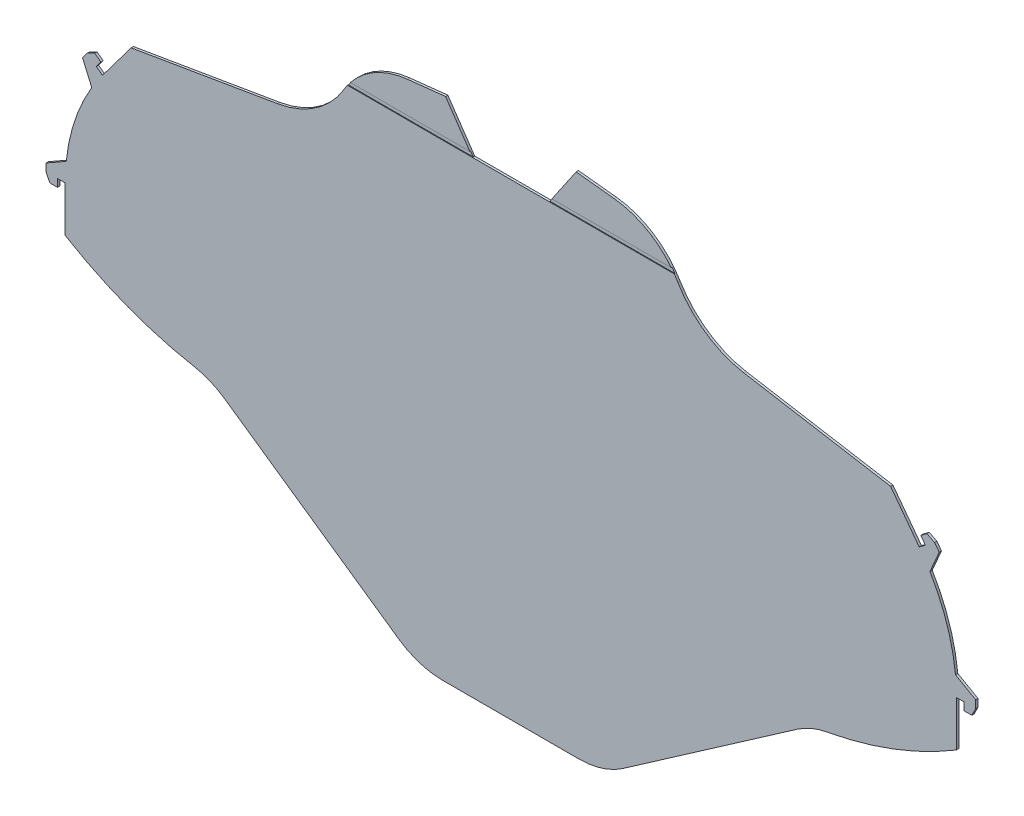
SolidWorks part; units mm, degrees
ref_plane "Front Plane" through (0, 0, 0) normal (0, 0, 1) x (1, 0, 0)
ref_plane "Top Plane" through (0, 0, 0) normal (0, 1, 0) x (1, 0, 0)
ref_plane "Right Plane" through (0, 0, 0) normal (1, 0, 0) x (0, 0, -1)
sketch "Sketch1" plane through (0, 0, 0) normal (0, 0, 1) x (1, 0, 0)
  line L0 (-24, -91.7648) -> (24, -91.7648)
  line L1 (0, 0) -> (0, -91.7648) construction
  line L2 (-10, 0) -> (-17, 10.2352)
  line L5 (-100.1804, -19.9556) -> (-60.7439, -13.2648)
  line L7 (-24, -91.7648) -> (-78.2662, -84.0567)
  line L8 (-17, 10.2352) -> (-26.9419, 9.1584)
  line L13 (-122.5, -58.7648) -> (122.5, -58.7648) construction
  line L14 (-60.7439, -13.2648) -> (-60.7439, -58.7648) construction
  line L15 (-113.5977, -28.7648) -> (-113.5977, -58.7648) construction
  line L16 (-10, 0) -> (10, 0)
  line L17 (10, 0) -> (17, 10.2352)
  line L18 (113.5977, -28.7648) -> (113.5977, -58.7648) construction
  line L19 (60.7439, -13.2648) -> (60.7439, -58.7648) construction
  line L20 (17, 10.2352) -> (26.9419, 9.1584)
  line L21 (24, -91.7648) -> (78.2662, -84.0567)
  line L22 (100.1804, -19.9556) -> (60.7439, -13.2648)
  line L23 (-17, 10.2352) -> (17, 10.2352) construction
  line L24 (0, 10.2352) -> (0, 0) construction
  arc A0 (-26.9419, 9.1584) -> (-43.4614, -1.4344) centre (-24.5729, -12.7137) ccw
  arc A1 (-43.4614, -1.4344) -> (-60.7439, -13.2648) centre (-64.9257, 11.383) cw
  arc A2 (-113.5977, -28.7648) -> (-100.1804, -19.9556) centre (-96.8349, -39.6739) cw
  arc A3 (-122.5, -58.7648) -> (-113.5977, -28.7648) centre (-67.5, -58.7648) cw
  arc A8 (-122.5, -58.7648) -> (-115.7111, -70.7648) centre (-108.5, -58.7648) ccw
  arc A9 (-115.7111, -70.7648) -> (-78.2662, -84.0567) centre (-64.2032, 14.9495) ccw
  arc A10 (115.7111, -70.7648) -> (78.2662, -84.0567) centre (64.2032, 14.9495) cw
  arc A11 (122.5, -58.7648) -> (115.7111, -70.7648) centre (108.5, -58.7648) cw
  arc A12 (122.5, -58.7648) -> (113.5977, -28.7648) centre (67.5, -58.7648) ccw
  arc A13 (113.5977, -28.7648) -> (100.1804, -19.9556) centre (96.8349, -39.6739) ccw
  arc A14 (43.4614, -1.4344) -> (60.7439, -13.2648) centre (64.9257, 11.383) ccw
  arc A15 (26.9419, 9.1584) -> (43.4614, -1.4344) centre (24.5729, -12.7137) cw
  dimension "D5" = 55
  dimension "D7" = 20
  dimension "D9" = 25
  dimension "D11" = 22
  dimension "D12" = 14
  dimension "D19" = 100
  dimension "D2" = 50.7439
  dimension "D3" = 102
  dimension "D4" = 10
  dimension "D6" = 14
  dimension "D8" = 40
  dimension "D10" = 58.7648
  dimension "D13" = 188.084
  dimension "D14" = 12.4
  dimension "D15" = 45.5
  dimension "D16" = 30
  dimension "D17" = 33
  dimension "D18" = 118.187
  dimension "D20" = 20
extrude "Main Shape" add sketch "Sketch1" along normal blind 0.6
sketch "Sketch2" plane through (0, 0, 0.6) normal (0, 0, 1) x (1, 0, 0)
  line L0 (0, 0) -> (0, -91.7648) construction
  line L1 (-24, -91.7648) -> (24, -91.7648) construction
  line L5 (-121, -58.7648) -> (-121, -56.7648)
  line L15 (-116, -58.7648) -> (-116, -70.5864)
  line L23 (113.5111, -43.4277) -> (119.6776, -41.3722) construction
  line L24 (113.5111, -43.4277) -> (106.4062, -22.1128) construction
  line L25 (110.3, -26.6648) -> (111.5, -28.2648)
  line L41 (-106.3, -29.6648) -> (-98.8487, -19.7297)
  line L42 (-60.7439, -13.2648) -> (-100.1804, -19.9556) construction
  line L43 (-98.8487, -19.7297) -> (-100.1804, -19.9556)
  line L44 (-116, -58.7648) -> (-118, -58.7648)
  line L45 (-118, -58.7648) -> (-118, -60.7648)
  line L46 (-118, -60.7648) -> (-120, -60.7648)
  line L47 (-120, -60.7648) -> (-121, -58.7648)
  line L48 (-121, -56.7648) -> (-115.7423, -53.7714)
  line L49 (-113.5111, -43.4277) -> (-106.4062, -22.1128) construction
  line L50 (-113.5111, -43.4277) -> (-119.6776, -41.3722) construction
  line L51 (-111.5, -28.2648) -> (-109.0898, -33.8141)
  line L52 (-108.3, -25.6648) -> (-110.3, -26.6648)
  line L53 (-106.7, -26.8648) -> (-108.3, -25.6648)
  line L54 (-107.9, -28.4648) -> (-106.7, -26.8648)
  line L55 (-106.3, -29.6648) -> (-107.9, -28.4648)
  line L56 (-110.3, -26.6648) -> (-111.5, -28.2648)
  line L57 (106.3, -29.6648) -> (107.9, -28.4648)
  line L58 (107.9, -28.4648) -> (106.7, -26.8648)
  line L59 (106.7, -26.8648) -> (108.3, -25.6648)
  line L60 (108.3, -25.6648) -> (110.3, -26.6648)
  line L61 (111.5, -28.2648) -> (109.0898, -33.8141)
  line L62 (121, -56.7648) -> (115.7423, -53.7714)
  line L63 (120, -60.7648) -> (121, -58.7648)
  line L64 (118, -60.7648) -> (120, -60.7648)
  line L65 (118, -58.7648) -> (118, -60.7648)
  line L66 (116, -58.7648) -> (118, -58.7648)
  line L67 (98.8487, -19.7297) -> (100.1804, -19.9556)
  line L68 (106.3, -29.6648) -> (98.8487, -19.7297)
  line L69 (116, -58.7648) -> (116, -70.5864)
  line L70 (121, -58.7648) -> (121, -56.7648)
  arc A9 (-106.3, -29.6648) -> (-116, -58.7648) centre (-67.5, -58.7648) ccw construction
  arc A11 (-113.5977, -28.7648) -> (-122.5, -58.7648) centre (-67.5, -58.7648) ccw construction
  arc A12 (-115.7423, -53.7714) -> (-109.0898, -33.8141) centre (-67.5, -58.7648) cw
  arc A13 (-107.5, -28.7648) -> (-117.5, -58.7648) centre (-67.5, -58.7648) ccw construction
  arc A14 (-105.1, -30.5648) -> (-114.5, -58.7648) centre (-67.5, -58.7648) ccw construction
  arc A15 (-105.1, -30.5648) -> (-107.5, -28.7648) centre (-106.3, -29.6648) ccw construction
  arc A16 (-117.5, -58.7648) -> (-114.5, -58.7648) centre (-116, -58.7648) ccw construction
  arc A18 (106.3, -29.6648) -> (116, -58.7648) centre (67.5, -58.7648) cw construction
  arc A19 (107.5, -28.7648) -> (117.5, -58.7648) centre (67.5, -58.7648) cw construction
  arc A21 (105.1, -30.5648) -> (114.5, -58.7648) centre (67.5, -58.7648) cw construction
  arc A22 (105.1, -30.5648) -> (107.5, -28.7648) centre (106.3, -29.6648) cw construction
  arc A23 (117.5, -58.7648) -> (114.5, -58.7648) centre (116, -58.7648) cw construction
  arc A24 (122.5, -58.7648) -> (116, -70.5864) centre (108.5, -58.7648) cw
  arc A25 (113.5977, -28.7648) -> (122.5, -58.7648) centre (67.5, -58.7648) cw
  arc A26 (100.1804, -19.9556) -> (113.5977, -28.7648) centre (96.8349, -39.6739) cw
  arc A33 (-122.5, -58.7648) -> (-115.7111, -70.7648) centre (-108.5, -58.7648) ccw construction
  arc A34 (-100.1804, -19.9556) -> (-113.5977, -28.7648) centre (-96.8349, -39.6739) ccw construction
  arc A35 (-100.1804, -19.9556) -> (-113.5977, -28.7648) centre (-96.8349, -39.6739) ccw
  arc A36 (-113.5977, -28.7648) -> (-122.5, -58.7648) centre (-67.5, -58.7648) ccw
  arc A37 (-122.5, -58.7648) -> (-116, -70.5864) centre (-108.5, -58.7648) ccw
  arc A38 (115.7423, -53.7714) -> (109.0898, -33.8141) centre (67.5, -58.7648) ccw
  point P24 (-113.5111, -43.4277)
  point P46 (113.5111, -43.4277)
  dimension "D1" = 1.5
  dimension "D2" = 5
  dimension "D3" = 2
  dimension "D7" = 5
  dimension "D4" = 2
  dimension "D5" = 2
  dimension "D6" = 2
  dimension "D8" = 5
extrude "Tabs" cut sketch "Sketch2" against normal through all both and the other way through all
sketch "Sketch4" plane through (0, 0, 0.6) normal (0, 0, 1) x (1, 0, 0)
  line L6 (-45, 0) -> (45, 0)
  line L8 (45, 0) -> (45, 1)
  line L9 (45, 1) -> (-45, 1)
  line L10 (-45, 1) -> (-45, 0)
  point P3 (0, 0)
  dimension "D1" = 90
  dimension "D2" = 1
extrude "Tab Fold Line" cut sketch "Sketch4" against normal blind 0.2
sketch "Sketch5" plane through (0, 0, 0.6) normal (0, 0, 1) x (1, 0, 0)
  line L0 (-78.2662, -84.0567) -> (-24, -121.7648)
  line L1 (-24, -121.7648) -> (24, -121.7648)
  line L2 (24, -121.7648) -> (78.2662, -84.0567)
  line L3 (-78.2662, -84.0567) -> (-24, -91.7648) construction
  line L4 (24, -91.7648) -> (78.2662, -84.0567) construction
  line L5 (-24, -91.7648) -> (24, -91.7648) construction
  line L6 (24, -91.7648) -> (78.2662, -84.0567)
  line L7 (-24, -91.7648) -> (24, -91.7648)
  line L8 (-78.2662, -84.0567) -> (-24, -91.7648)
  point P6 (0, 0)
  point P7 (0, 0)
  point P10 (19, -135.0911)
  point P12 (-19, -128.8488)
  dimension "D1" = 30
extrude "Chin guard" add sketch "Sketch5" against normal up to surface (0.6 mm away) up to face at (0, -39.2266, 0)
fillet "Fillet1" radius 20 4 edges at (-78.2662, -84.0567, 0.3) (78.2662, -84.0567, 0.3) (24, -121.7648, 0.3) (-24, -121.7648, 0.3)
